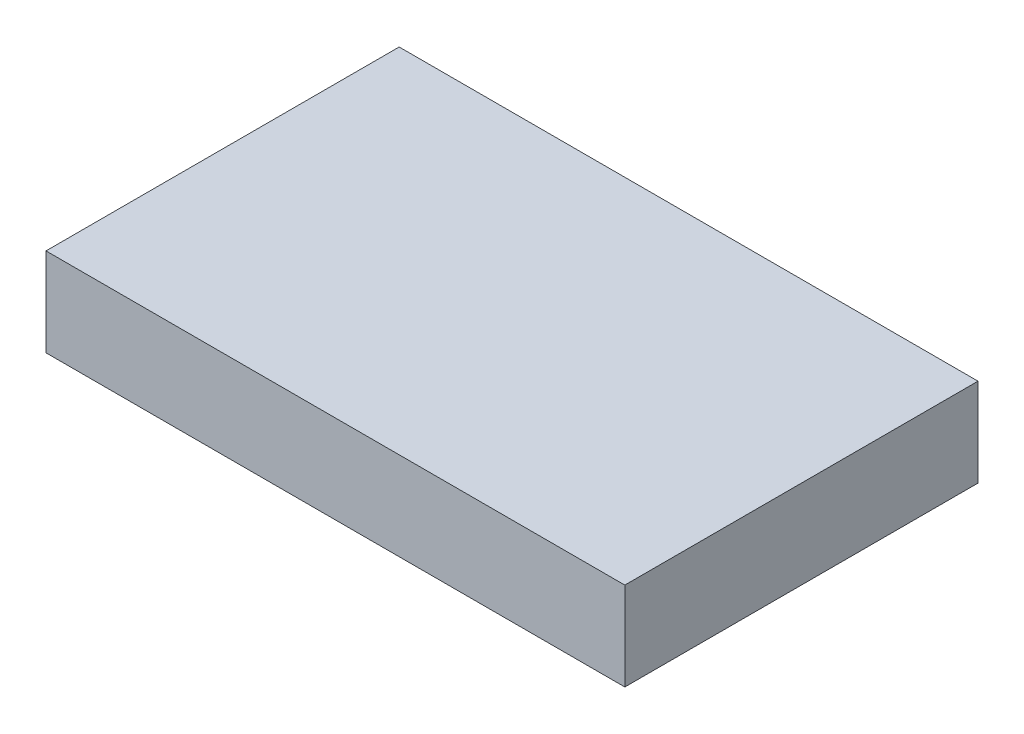
SolidWorks part; units mm, degrees
ref_plane "Front Plane" through (0, 0, 0) normal (0, 0, 1) x (1, 0, 0)
ref_plane "Top Plane" through (0, 0, 0) normal (0, 1, 0) x (1, 0, 0)
ref_plane "Right Plane" through (0, 0, 0) normal (1, 0, 0) x (0, 0, -1)
sketch "Sketch1" plane through (0, 0, 0) normal (0, 1, 0) x (1, 0, 0)
  line L1 (-29.5, 18) -> (29.5, 18)
  line L2 (-29.5, 18) -> (-29.5, -18)
  line L3 (-29.5, -18) -> (29.5, -18)
  line L4 (29.5, 18) -> (29.5, -18)
  line L5 (-29.5, 18) -> (29.5, -18) construction
  line L6 (-29.5, -18) -> (29.5, 18) construction
  point P0 (0, 0)
  dimension "D1" = 36
  dimension "D2" = 59
extrude "Boss-Extrude1" add sketch "Sketch1" along normal blind 9
